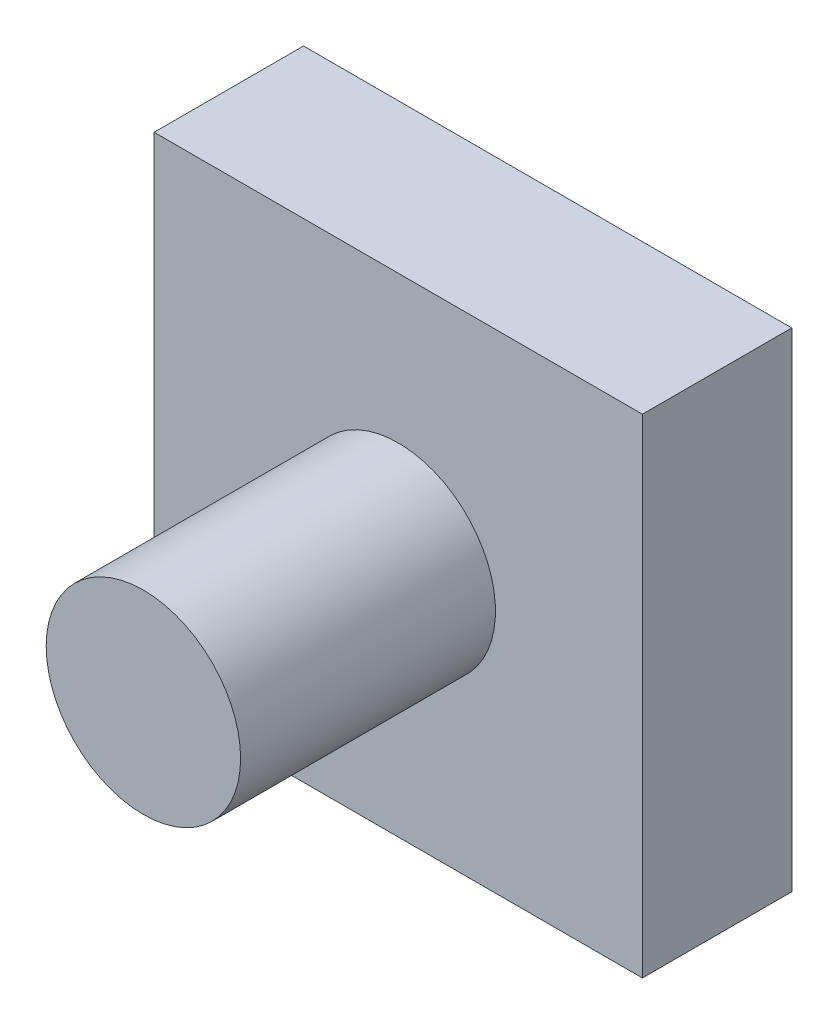
SolidWorks part; units mm, degrees
ref_plane "Front Plane" through (0, 0, 0) normal (0, 0, 1) x (1, 0, 0)
ref_plane "Top Plane" through (0, 0, 0) normal (0, 1, 0) x (1, 0, 0)
ref_plane "Right Plane" through (0, 0, 0) normal (1, 0, 0) x (0, 0, -1)
sketch "Sketch1" plane through (0, 0, 0) normal (0, 0, 1) x (1, 0, 0)
  line L1 (-17.6403, -17.6403) -> (17.6403, -17.6403)
  line L2 (-17.6403, -17.6403) -> (-17.6403, 17.6403)
  line L3 (-17.6403, 17.6403) -> (17.6403, 17.6403)
  line L4 (17.6403, -17.6403) -> (17.6403, 17.6403)
  line L5 (-17.6403, -17.6403) -> (17.6403, 17.6403) construction
  line L6 (-17.6403, 17.6403) -> (17.6403, -17.6403) construction
  point P0 (0, 0)
  dimension "D1" = 35.2806
  dimension "D2" = 35.2806
extrude "Extrude1" add sketch "Sketch1" along normal blind 10.795
sketch "Sketch2" plane through (0, 0, 10.795) normal (0, 0, 1) x (1, 0, 0)
  circle A0 centre (0, 0) radius 7.0231
  dimension "D1" = 14.0462
extrude "Extrude2" add sketch "Sketch2" along normal blind 18.415
sketch "Sketch3" plane through (-17.6403, 0, 0) normal (-1, 0, 0) x (0, 0, 1)
  line L0 (5.3975, 17.6403) -> (5.3975, 6.9723) construction
  line L1 (10.795, 17.6403) -> (0, 17.6403) construction
  line L2 (5.3975, -17.6403) -> (5.3975, -6.9723) construction
  line L3 (10.795, -17.6403) -> (0, -17.6403) construction
  dimension "D1" = 10.668
